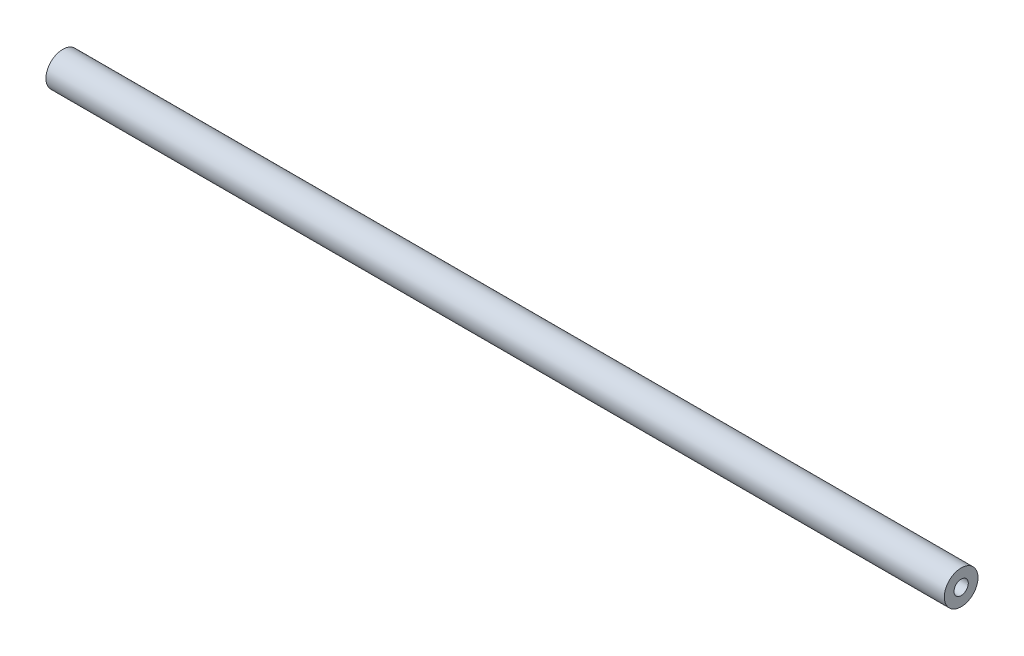
SolidWorks part; units mm, degrees
material "7075-T6 (SN)"
ref_plane "Front Plane" through (0, 0, 0) normal (0, 0, 1) x (1, 0, 0)
ref_plane "Top Plane" through (0, 0, 0) normal (0, 1, 0) x (1, 0, 0)
ref_plane "Right Plane" through (0, 0, 0) normal (1, 0, 0) x (0, 0, -1)
sketch "Sketch1" plane through (0, 0, 0) normal (1, 0, 0) x (0, 0, -1)
  circle A1 centre (0, 0) radius 4.7625
  dimension "D1" = 9.525
extrude "Boss-Extrude1" add sketch "Sketch1" along normal mid plane 254
hole_wizard "#10-32 Tapped Hole1" positions "3DSketch1" profile "Sketch2" tap size "#10-32" standard "ANSI Inch"
sketch3d "3DSketch1"
  line L0 (127, 0, 0) -> (-127, 0, 0) construction
  point P0 (127, 0, 0)
  point P7 (-127, 0, 0)
sketch "Sketch2" plane through (127, 0, 0) normal (0, 1, 0) x (0, 0, -1)
  line L0 (0, 0) -> (0, 13.2428)
  line L1 (0, 13.2428) -> (2.0193, 12.0294)
  line L2 (2.0193, 12.0294) -> (2.0193, 0)
  line L5 (2.0193, 0) -> (0, 0)
  line L10 (0, 13.2428) -> (-2.0193, 12.0294) construction
  line L11 (0, -6.35) -> (0, 107.95) construction
  dimension "Tap Drill Dia." = 4.0386
  dimension "Tap Drill Depth" = 12.0294
  dimension "Drill Angle" = 118
cosmetic thread "Hole Thread1"
cosmetic thread "Hole Thread2"
